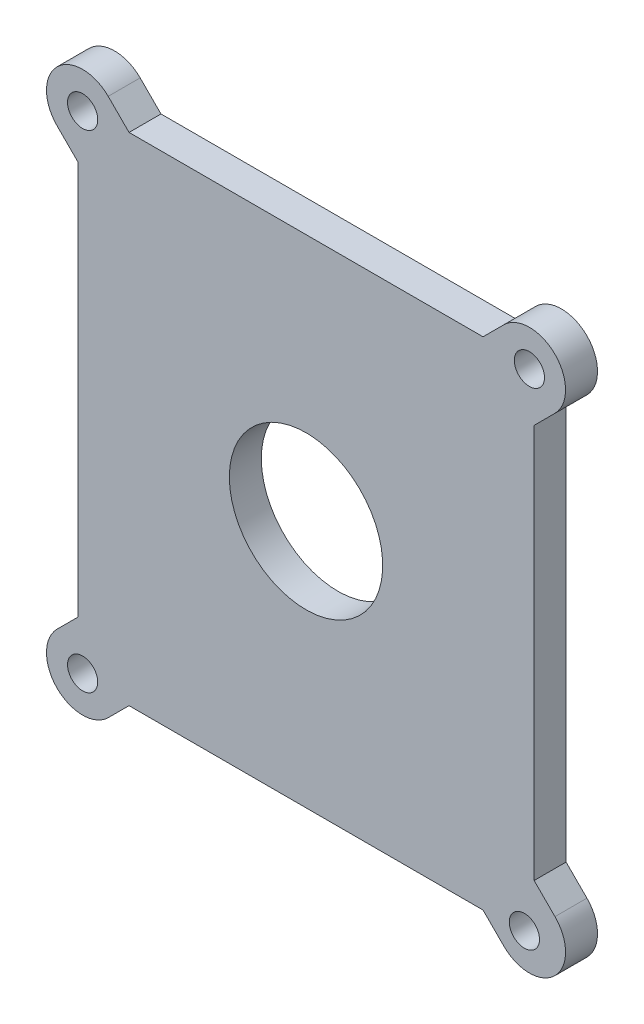
SolidWorks part; units mm, degrees
material "Custom Plastic"
ref_plane "X-Y Datum" through (0, 0, 0) normal (0, 0, 1) x (1, 0, 0)
ref_plane "X-Z Datum" through (0, 0, 0) normal (0, 1, 0) x (1, 0, 0)
ref_plane "Y-Z Datum" through (0, 0, 0) normal (1, 0, 0) x (0, 0, -1)
sketch "Sketch1" plane through (0, 0, 0) normal (0, 0, 1) x (1, 0, 0)
  line L0 (33.9979, 36.9951) -> (33.9979, -36.9951)
  line L1 (-33.9979, -36.9951) -> (33.9979, -36.9951)
  line L2 (-33.9979, -36.9951) -> (-33.9979, 36.9951)
  line L3 (-33.9979, 36.9951) -> (33.9979, 36.9951)
  line L5 (-33.9979, -36.9951) -> (33.9979, 36.9951) construction
  line L6 (-33.9979, 36.9951) -> (33.9979, -36.9951) construction
  line L7 (26.3779, -36.9951) -> (26.3779, -29.3751)
  line L9 (26.3779, -29.3751) -> (33.9979, -29.3751)
  line L13 (26.3779, -36.9951) -> (29.4839, -40.1011)
  line L14 (33.9979, -29.3751) -> (37.1039, -32.4811)
  line L15 (33.9264, -36.9951) -> (33.9979, -36.9236)
  arc A1 (29.4839, -40.1011) -> (37.1039, -32.4811) centre (33.2939, -36.2911) ccw
  circle A2 centre (0, 0) radius 11.43
  point P0 (0, 0)
  dimension "D3" = 22.86
  dimension "D1" = 7.62
  dimension "D2" = 7.62
extrude "Boss-Extrude1" add sketch "Sketch1" along normal blind 4.7625
mirror "Mirror1" about plane through (0, 0, 0) normal (0, 1, 0) of "Boss-Extrude1"
mirror "Mirror2" about plane through (0, 0, 0) normal (1, 0, 0) of "Mirror1", "Boss-Extrude1"
sketch "Sketch3" plane through (0, 0, 4.7625) normal (0, 0, 1) x (1, 0, 0)
  line L0 (0, 0) -> (29.1039, -32.956) construction
  line L1 (29.1039, -32.956) -> (32.5472, -36.5867) construction
  line L2 (32.5472, -36.5867) -> (37.0392, -41.3231) construction
  circle A0 centre (32.5472, -36.5867) radius 2.9591
  circle A1 centre (32.5472, -36.5867) radius 5.4991
sketch "Sketch7" plane through (0, 0, 4.7625) normal (0, 0, 1) x (1, 0, 0)
  point P0 (32.5472, -36.5867)
  point P1 (-33.2939, -36.2911)
  point P3 (33.2939, 36.2911)
  point P5 (-33.2939, 36.2911)
hole_wizard "M4 Clearance Hole2" positions "Sketch8" profile "Sketch9" hole size "M4" standard "ANSI Metric" end condition through all
sketch "Sketch8" plane through (0, 0, 4.7625) normal (0, 0, 1) x (1, 0, 0)
  point P0 (-33.2939, 36.2911)
  point P3 (33.2939, 36.2911)
  point P6 (32.5472, -36.5867)
  point P9 (-33.2939, -36.2911)
sketch "Sketch9" plane through (-33.2939, 36.2911, 4.7625) normal (1, 0, 0) x (0, -1, 0)
  line L0 (0, 0) -> (0, 4.7625)
  line L1 (0, 4.7625) -> (2.25, 4.7625)
  line L2 (2.25, 4.7625) -> (2.25, 0)
  line L5 (2.25, 0) -> (0, 0)
  line L11 (0, -6.35) -> (0, 107.95) construction
  dimension "Thru Hole Dia." = 4.5
  dimension "Thru Hole Depth" = 4.7625
